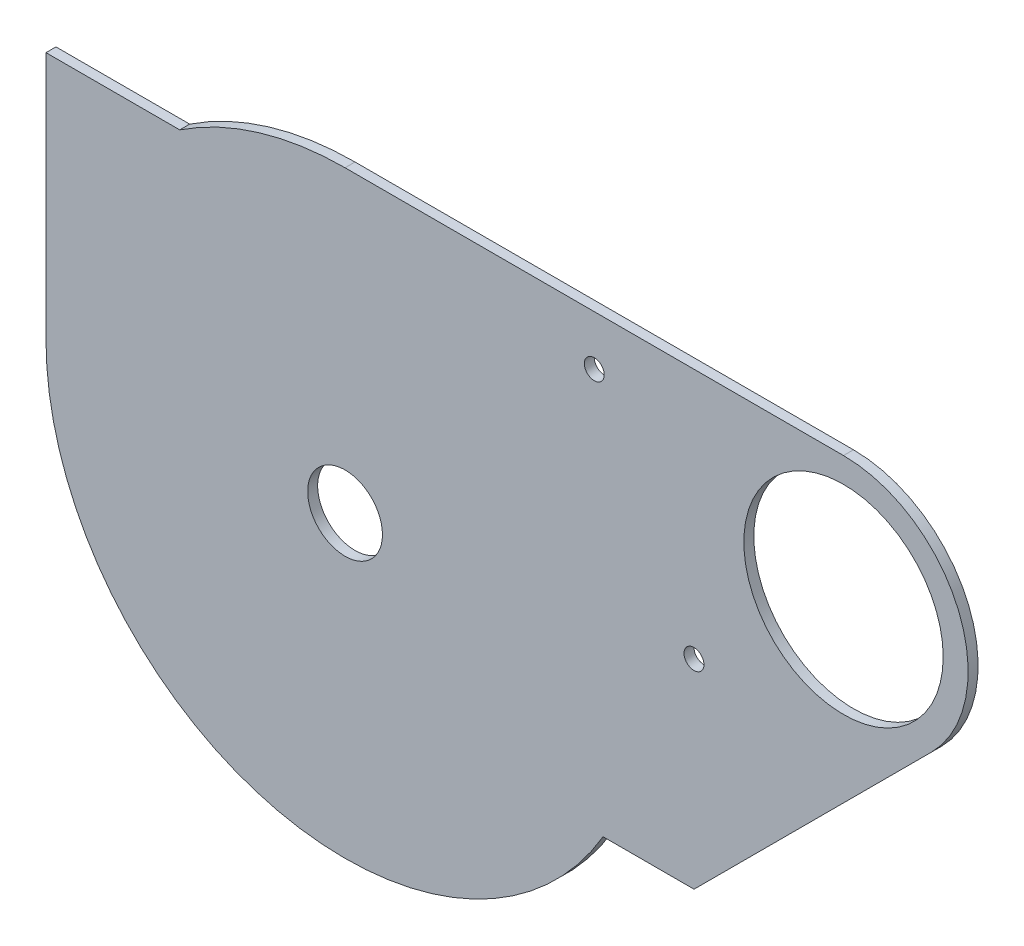
SolidWorks part; units mm, degrees
ref_plane "前视基准面" through (0, 0, 0) normal (0, 0, 1) x (1, 0, 0)
ref_plane "上视基准面" through (0, 0, 0) normal (0, 1, 0) x (1, 0, 0)
ref_plane "右视基准面" through (0, 0, 0) normal (1, 0, 0) x (0, 0, -1)
sketch "Sketch1" plane through (0, 0, 0) normal (0, 0, 1) x (1, 0, 0)
  line L0 (-26.5591, 60) -> (97.717, 60) construction
  line L3 (-33.1662, 50) -> (-60, 50)
  line L4 (-60, 0) -> (-60, 50)
  line L5 (100, 60) -> (0, 60)
  line L6 (70.01, -30.3453) -> (83.7655, -16.5899) construction
  line L7 (83.7655, -16.5899) -> (117.6777, 17.3223) construction
  line L8 (117.6777, 17.3223) -> (70.01, -30.3453)
  line L9 (70.01, -30.3453) -> (51.7606, -30.3453)
  arc A0 (0, 60) -> (51.7606, -30.3453) centre (0, 0) ccw
  arc A1 (117.6777, 17.3223) -> (100, 60) centre (100, 35) ccw
  circle A2 centre (0, 0) radius 7.5
  circle A3 centre (100, 35) radius 20
  dimension "D1" = 120
  dimension "D2" = 100
  dimension "D3" = 25
  dimension "D4" = 40
extrude "Boss-Extrude1" add sketch "Sketch1" along normal blind 2 contours A0 L3 L4 | L8 A1 L5 A0 L9 A3 A2
sketch "Sketch3" plane through (0, 0, 2) normal (0, 0, 1) x (1, 0, 0)
  line L0 (100, 60) -> (0, 60) construction
  line L2 (-60, 0) -> (-60, 50) construction
  line L3 (70.01, -30.3453) -> (51.7606, -30.3453) construction
  circle A0 centre (50, 50) radius 2
  circle A1 centre (70, 9.6547) radius 2
  point P8 (-60, 38.1895)
  dimension "D1" = 10
  dimension "D2" = 110
  dimension "D3" = 40
  dimension "D4" = 130
  dimension "D5" = 4
extrude "Cut-Extrude1" cut sketch "Sketch3" against normal up to next
